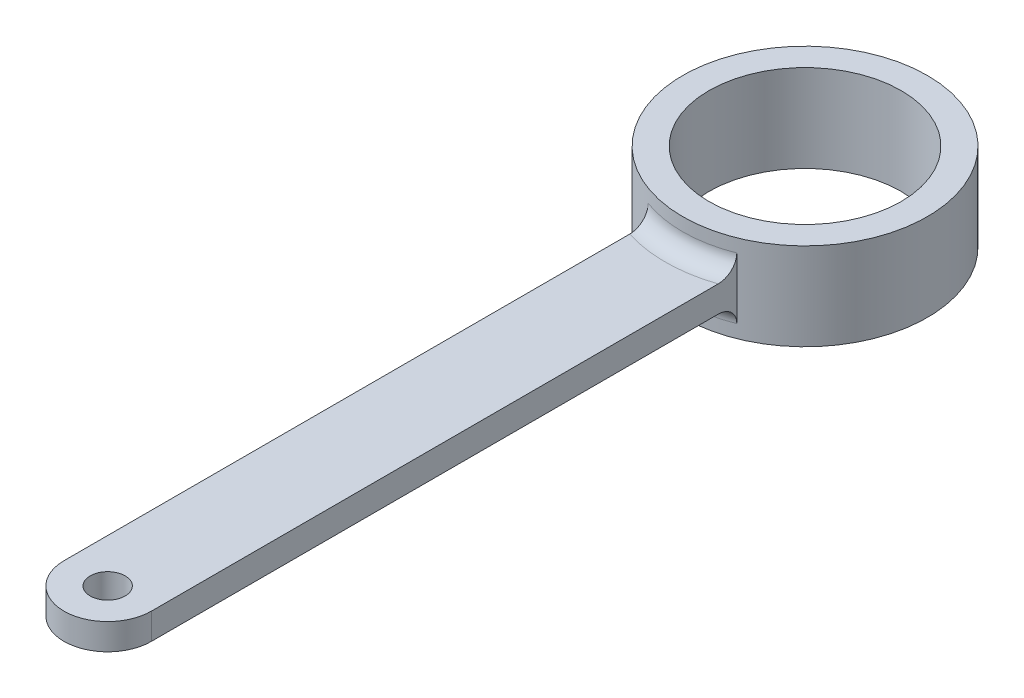
SolidWorks part; units mm, degrees
material "Wrought Copper"
ref_plane "Front Plane" through (0, 0, 0) normal (0, 0, 1) x (1, 0, 0)
ref_plane "Top Plane" through (0, 0, 0) normal (0, 1, 0) x (1, 0, 0)
ref_plane "Right Plane" through (0, 0, 0) normal (1, 0, 0) x (0, 0, -1)
sketch "Sketch1" plane through (0, 0, 0) normal (0, 1, 0) x (1, 0, 0)
  circle A0 centre (0, 0) radius 7
  circle A1 centre (0, 0) radius 5.5
  dimension "D1" = 14
  dimension "D2" = 11
extrude "Boss-Extrude1" add sketch "Sketch1" along normal mid plane 5
sketch "Sketch2" plane through (0, 0, 0) normal (0, 1, 0) x (1, 0, 0)
  line L0 (2.5957, -40) -> (2.5957, -6.501)
  line L1 (-2.4043, -40) -> (-2.4043, -6.5741)
  arc A0 (-2.4043, -40) -> (2.5957, -40) centre (0.0957, -40) ccw
  circle A1 centre (0.0957, -40) radius 1
  circle A3 centre (0, 0) radius 7
  arc A4 (-2.4043, -6.5741) -> (2.5957, -6.501) centre (0, 0) ccw
  dimension "D1" = 5
  dimension "D2" = 2
  dimension "D4" = 40
  dimension "D3" = 0
extrude "Boss-Extrude2" add sketch "Sketch2" along normal mid plane 1.5
fillet "Fillet1" radius 1 2 edges at (0.1024, -0.75, 6.9993) (0.1024, 0.75, 6.9993)
